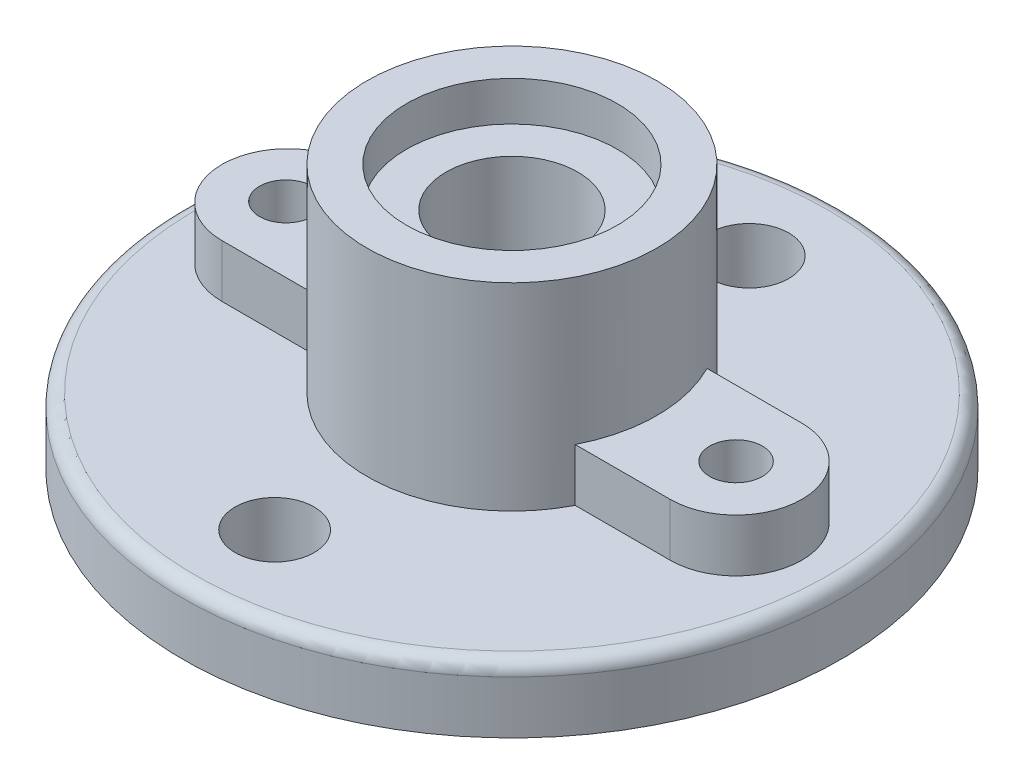
SolidWorks part; units mm, degrees
ref_plane "前基準面" through (0, 0, 0) normal (0, 0, 1) x (1, 0, 0)
ref_plane "上基準面" through (0, 0, 0) normal (0, 1, 0) x (1, 0, 0)
ref_plane "右基準面" through (0, 0, 0) normal (1, 0, 0) x (0, 0, -1)
sketch "草圖1" plane through (0, 0, 0) normal (0, 0, 1) x (1, 0, 0)
  line L0 (-0.4117, 0) -> (0, 0)
  line L1 (0, 0) -> (0, 20)
  line L2 (0, 20) -> (11, 20)
  line L3 (11, 20) -> (11, 5)
  line L4 (11, 5) -> (25, 5)
  line L5 (25, 5) -> (25, 0)
  line L6 (25, 0) -> (0, 0)
  point P3 (0, 10)
  dimension "D1" = 25
  dimension "D2" = 5
  dimension "D3" = 20
  dimension "D4" = 11
revolve "旋轉1" add sketch "草圖1" angle 360 about L1
sketch "草圖2" plane through (0, 0, 0) normal (0, 0, 1) x (1, 0, 0)
  line L0 (0, 20) -> (0, 0)
  line L1 (11, 20) -> (-11, 20) construction
  line L2 (0, 0) -> (5, 0)
  line L3 (-25, 0) -> (25, 0) construction
  line L4 (5, 0) -> (5, 17)
  line L5 (5, 17) -> (8, 17)
  line L6 (8, 17) -> (8, 20)
  line L7 (8, 20) -> (0, 20)
  dimension "D1" = 5
  dimension "D2" = 8
  dimension "D3" = 3
revolve "除料-旋轉1" cut sketch "草圖2" angle 360 about L0
sketch "草圖3" plane through (0, 0, 0) normal (0, 1, 0) x (1, 0, 0)
  line L0 (-17, 5) -> (-9.798, 5)
  line L1 (-17, -5) -> (-9.798, -5)
  line L2 (-9.798, 5) -> (-9.798, -5)
  line L3 (9.798, 5) -> (9.798, -5)
  line L4 (9.798, -5) -> (17, -5)
  line L5 (9.798, 5) -> (17, 5)
  arc A5 (-17, 5) -> (-17, -5) centre (-17, 0) ccw
  arc A6 (17, -5) -> (17, 5) centre (17, 0) ccw
  circle A7 centre (0, 0) radius 11 construction
  circle A8 centre (0, 0) radius 11 construction
  dimension "D7" = 17
  dimension "D9" = 10
  dimension "D10" = 10
  dimension "D5" = 34
extrude "填料-伸長2" add sketch "草圖3" along normal blind 9 contours L0 L2 L1 A5 | A6 L5 L3 L4
sketch "草圖4" plane through (0, 0, 0) normal (0, 1, 0) x (1, 0, 0)
  circle A0 centre (-17.1424, 0) radius 2
  circle A1 centre (17, 0) radius 2
  circle A2 centre (0, 18) radius 3
  circle A3 centre (0, -18) radius 3
  point P8 (0, 0)
  point P11 (16.5743, -0.8588)
  dimension "D1" = 4
  dimension "D2" = 4
  dimension "D3" = 6
  dimension "D4" = 6
  dimension "D5" = 18
  dimension "D6" = 18
  dimension "D7" = 34.1424
  dimension "D8" = 17
extrude "除料-伸長1" cut sketch "草圖4" along normal blind 9
fillet "圓角1" radius 1 1 edges at (0, 5, -25)
